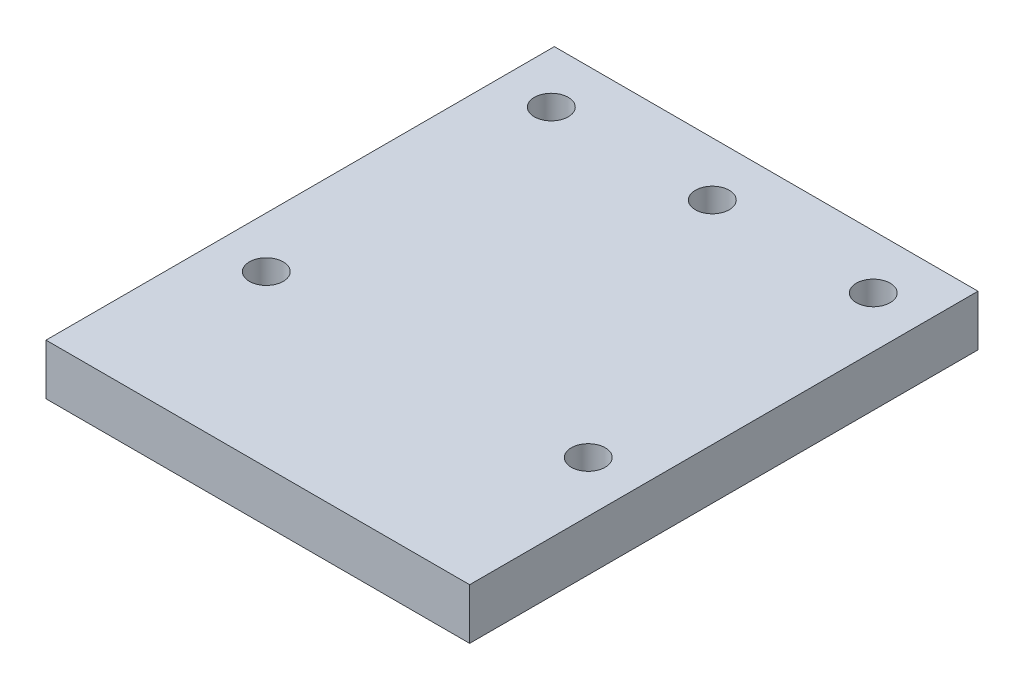
SolidWorks part; units mm, degrees
material "AISI 316 Stainless Steel Sheet (SS)"
ref_plane "Front Plane" through (0, 0, 0) normal (0, 0, 1) x (1, 0, 0)
ref_plane "Top Plane" through (0, 0, 0) normal (0, 1, 0) x (1, 0, 0)
ref_plane "Right Plane" through (0, 0, 0) normal (1, 0, 0) x (0, 0, -1)
sketch "Sketch1" plane through (0, 0, 0) normal (0, 1, 0) x (1, 0, 0)
  line L1 (0, 0) -> (25, 0)
  line L2 (0, 0) -> (0, -30)
  line L3 (0, -30) -> (25, -30)
  line L4 (25, 0) -> (25, -30)
  line L5 (5, 0) -> (20, 0) construction
  line L6 (5, 0) -> (5, -25) construction
  line L7 (5, -25) -> (20, -25) construction
  line L8 (20, 0) -> (20, -25) construction
  line L9 (7.5, -12.7) -> (17.5, -12.7) construction
  line L10 (7.5, -12.7) -> (7.5, 0) construction
  line L11 (7.5, 0) -> (17.5, 0) construction
  line L12 (17.5, -12.7) -> (17.5, 0) construction
  circle A0 centre (12.5, -3.18) radius 1
  circle A1 centre (3, -20) radius 1
  circle A2 centre (22, -20) radius 1
  circle A3 centre (22, -3.18) radius 1
  circle A4 centre (3, -3.18) radius 1
  point P8 (12.5, 0)
  point P10 (12.5, -25)
  point P21 (0, 0)
  point P22 (30.0511, -12.5)
  point P23 (12.5, -12.7)
  dimension "D2" = 2
  dimension "D8" = 2
  dimension "D1" = 25
  dimension "D3" = 3.18
  dimension "D4" = 30
  dimension "D5" = 3.18
  dimension "D6" = 3
  dimension "D7" = 3
  dimension "D9" = 15
  dimension "D10" = 3.18
  dimension "D11" = 25
  dimension "D12" = 10
  dimension "D13" = 20
  dimension "D14" = 12.7
extrude "Boss-Extrude1" add sketch "Sketch1" along normal blind 3
